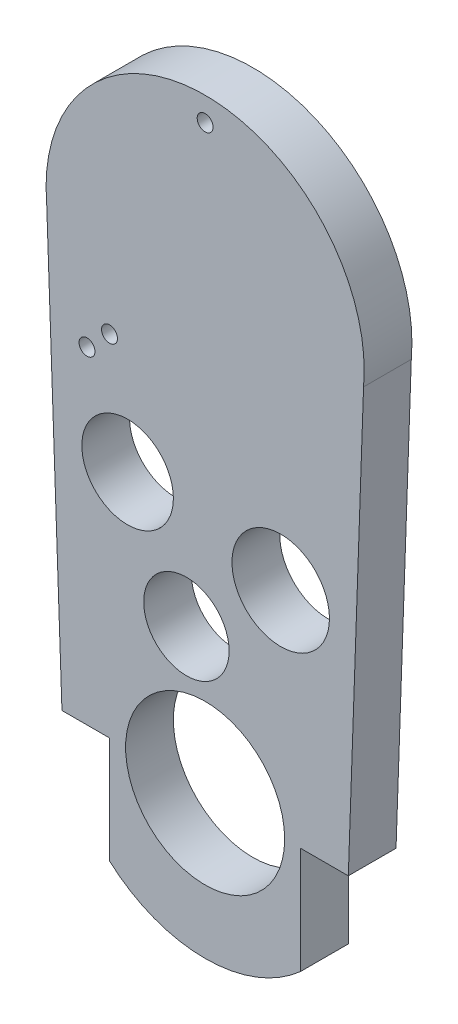
SolidWorks part; units mm, degrees
ref_plane "Plan de face" through (0, 0, 0) normal (0, 0, 1) x (1, 0, 0)
ref_plane "Plan de dessus" through (0, 0, 0) normal (0, 1, 0) x (1, 0, 0)
ref_plane "Plan de droite" through (0, 0, 0) normal (1, 0, 0) x (0, 0, -1)
sketch "Esquisse1" plane through (0, 0, 0) normal (0, 0, 1) x (1, 0, 0)
  line L0 (8.3168, 9) -> (0, 9) construction
  line L1 (0, 9) -> (0, 6) construction
  line L2 (0, 6) -> (8.0445, 6) construction
  line L3 (0, 0) -> (0, 28) construction
  line L4 (-7.5, 0) -> (-9.9591, 27.0962) construction
  line L5 (9.9591, 27.0962) -> (7.5, 0) construction
  line L6 (9.9591, 27.0962) -> (8.3168, 9) construction
  line L7 (8.0445, 6) -> (7.5, 0) construction
  line L8 (0, 0) -> (18.0723, 0) construction
  line L9 (7.5, 0) -> (6.6832, -9) construction
  line L12 (6.6832, -9) -> (0, -9) construction
  line L13 (0, -9) -> (0, -6) construction
  line L14 (0, -6) -> (-6.9555, -6) construction
  line L15 (-6.9555, -6) -> (-7.5, 0) construction
  line L16 (6, -6.7082) -> (6, 0)
  line L17 (6, 0) -> (9, 0)
  line L18 (9, 0) -> (9.9591, 27.0962)
  line L20 (-9, 0) -> (-9.9591, 27.0962)
  line L22 (-6, -6.7082) -> (-6, 0)
  line L23 (-6, 0) -> (-9, 0)
  line L24 (-7.4246, 20.5754) -> (0, 28) construction
  circle A0 centre (0, 0) radius 5
  circle A1 centre (0, 28) radius 10 construction
  arc A2 (-9.9591, 27.0962) -> (9.9591, 27.0962) centre (0, 28) cw
  arc A4 (9, 0) -> (-9, 0) centre (0, 0) cw construction
  arc A5 (-6, -6.7082) -> (6, -6.7082) centre (0, 0) ccw
  circle A6 centre (-4.8742, 15.0481) radius 2.8775
  circle A7 centre (4.7507, 13.4162) radius 3.0635
  circle A8 centre (-1.1774, 8.4871) radius 2.6843
  circle A9 centre (-7.4246, 20.5754) radius 0.5
  circle A10 centre (-6.0104, 21.9896) radius 0.5
  circle A11 centre (0, 28) radius 9 construction
  circle A12 centre (0, 36.5) radius 0.5
  dimension "D1" = 10
  dimension "D4" = 10
  dimension "D13" = 1
  dimension "D14" = 1
  dimension "D2" = 3
  dimension "D3" = 9
  dimension "D7" = 28
  dimension "D5" = 15
  dimension "D6" = 15
  dimension "D8" = 9
  dimension "D9" = 3
  dimension "D10" = 3
  dimension "D12" = 6
  dimension "D11" = 1
  dimension "D15" = 45
extrude "Boss.-Extru.1" add sketch "Esquisse1" along normal blind 3
equation "\"D8@Esquisse1\"=\"D3@Esquisse1\""
equation "\"D9@Esquisse1\"=\"D2@Esquisse1\""
